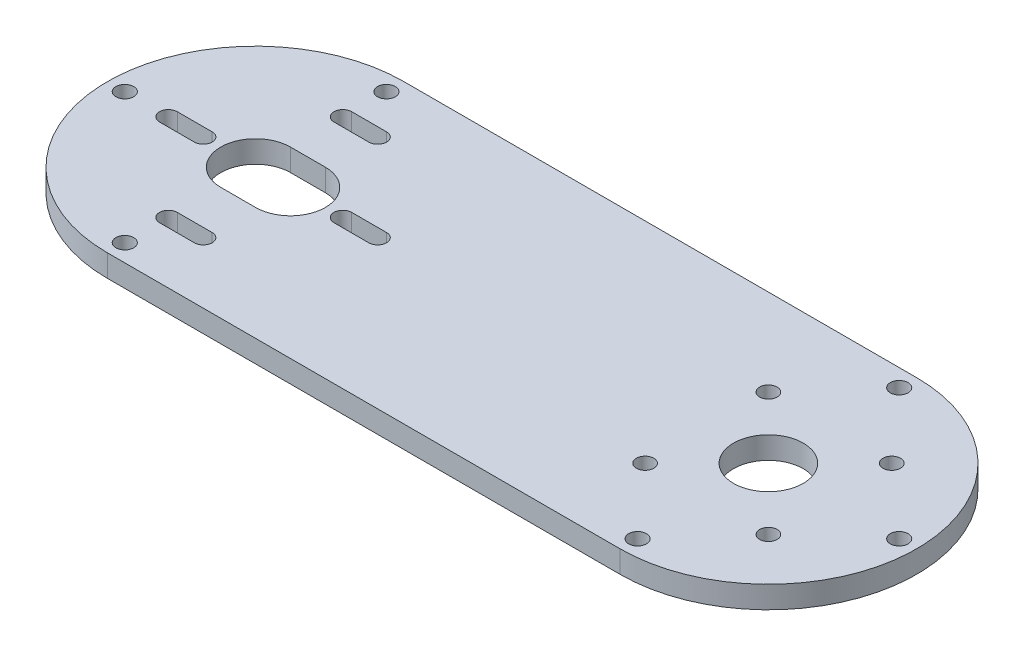
SolidWorks part; units mm, degrees
ref_plane "Front Plane" through (0, 0, 0) normal (0, 0, 1) x (1, 0, 0)
ref_plane "Top Plane" through (0, 0, 0) normal (0, 1, 0) x (1, 0, 0)
ref_plane "Right Plane" through (0, 0, 0) normal (1, 0, 0) x (0, 0, -1)
sketch "Sketch1" plane through (0, 0, 0) normal (0, 1, 0) x (1, 0, 0)
  line L0 (-147, 0) -> (0, 0) construction
  line L1 (-147, 42.5) -> (0, 42.5)
  line L6 (-147, -42.5) -> (0, -42.5)
  line L7 (-147, 0) -> (-137, 0) construction
  line L10 (-147, 10) -> (-137, 10)
  line L13 (-147, -10) -> (-137, -10)
  line L16 (-147, 25) -> (-137, 25) construction
  line L19 (17.6777, -17.6777) -> (-17.6777, 17.6777) construction
  line L20 (-147, 27.55) -> (-137, 27.55)
  line L21 (-17.6777, -17.6777) -> (17.6777, 17.6777) construction
  line L24 (-147, 22.45) -> (-137, 22.45)
  line L29 (-147, -25) -> (-137, -25) construction
  line L30 (-147, -22.45) -> (-137, -22.45)
  line L31 (-147, -27.55) -> (-137, -27.55)
  line L32 (-122, 0) -> (-112, 0) construction
  line L33 (-122, 2.55) -> (-112, 2.55)
  line L34 (-122, -2.55) -> (-112, -2.55)
  line L35 (-172, 0) -> (-162, 0) construction
  line L36 (-172, 2.55) -> (-162, 2.55)
  line L37 (-172, -2.55) -> (-162, -2.55)
  line L39 (0, 0) -> (-142, 0) construction
  line L40 (0, 0) -> (0, -89.6752) construction
  line L41 (0, -89.6752) -> (-142, -89.6752) construction
  line L42 (-142, 0) -> (-142, -89.6752) construction
  circle A1 centre (-147, 0) radius 10 construction
  circle A4 centre (-147, 0) radius 14.2875 construction
  circle A5 centre (0, 0) radius 10
  circle A8 centre (-147, 0) radius 37.5 construction
  circle A13 centre (-147, 0) radius 42.5
  circle A14 centre (0, 0) radius 42.5
  circle A15 centre (0, 0) radius 37.5 construction
  circle A16 centre (0, 37.5) radius 2.55
  circle A17 centre (37.5, 0) radius 2.55
  circle A18 centre (0, -37.5) radius 2.55
  circle A19 centre (-37.5, 0) radius 2.55 construction
  circle A29 centre (0, 0) radius 25 construction
  circle A30 centre (-17.6777, 17.6777) radius 2.5
  circle A31 centre (17.6777, -17.6777) radius 2.5
  circle A32 centre (-17.6777, -17.6777) radius 2.5
  circle A33 centre (17.6777, 17.6777) radius 2.5
  circle A38 centre (-184.5, 0) radius 2.55
  circle A39 centre (-147, 37.5) radius 2.55
  circle A40 centre (-147, -37.5) radius 2.55
  circle A41 centre (-109.5, 0) radius 2.55 construction
  arc A42 (-147, 10) -> (-147, -10) centre (-147, 0) ccw
  arc A43 (-137, -10) -> (-137, 10) centre (-137, 0) ccw
  circle A44 centre (-147, 0) radius 25 construction
  arc A45 (-147, 27.55) -> (-147, 22.45) centre (-147, 25) ccw
  arc A46 (-137, 22.45) -> (-137, 27.55) centre (-137, 25) ccw
  arc A47 (-147, -22.45) -> (-147, -27.55) centre (-147, -25) ccw
  arc A48 (-137, -27.55) -> (-137, -22.45) centre (-137, -25) ccw
  arc A49 (-122, 2.55) -> (-122, -2.55) centre (-122, 0) ccw
  arc A50 (-112, -2.55) -> (-112, 2.55) centre (-112, 0) ccw
  arc A51 (-172, 2.55) -> (-172, -2.55) centre (-172, 0) ccw
  arc A52 (-162, -2.55) -> (-162, 2.55) centre (-162, 0) ccw
  point P31 (-142, 0)
  point P41 (-142, 25)
  point P46 (-142, -25)
  point P62 (-117, 0)
  point P66 (0, 36.2835)
  point P77 (-167, 0)
  dimension "D2" = 20
  dimension "D4" = 5.1
  dimension "D5" = 45
  dimension "D6" = 28.575
  dimension "D7" = 20
  dimension "D9" = 142
  dimension "D10" = 85
  dimension "D8" = 75
  dimension "D11" = 5.1
  dimension "D12" = 75
  dimension "D13" = 50
  dimension "D14" = 50
  dimension "D15" = 5
  dimension "D16" = 10
  dimension "D20" = 10
  dimension "D3" = 147
  dimension "D17" = 5.1
  dimension "D21" = 20
extrude "Boss-Extrude1" add sketch "Sketch1" against normal blind 6.35
